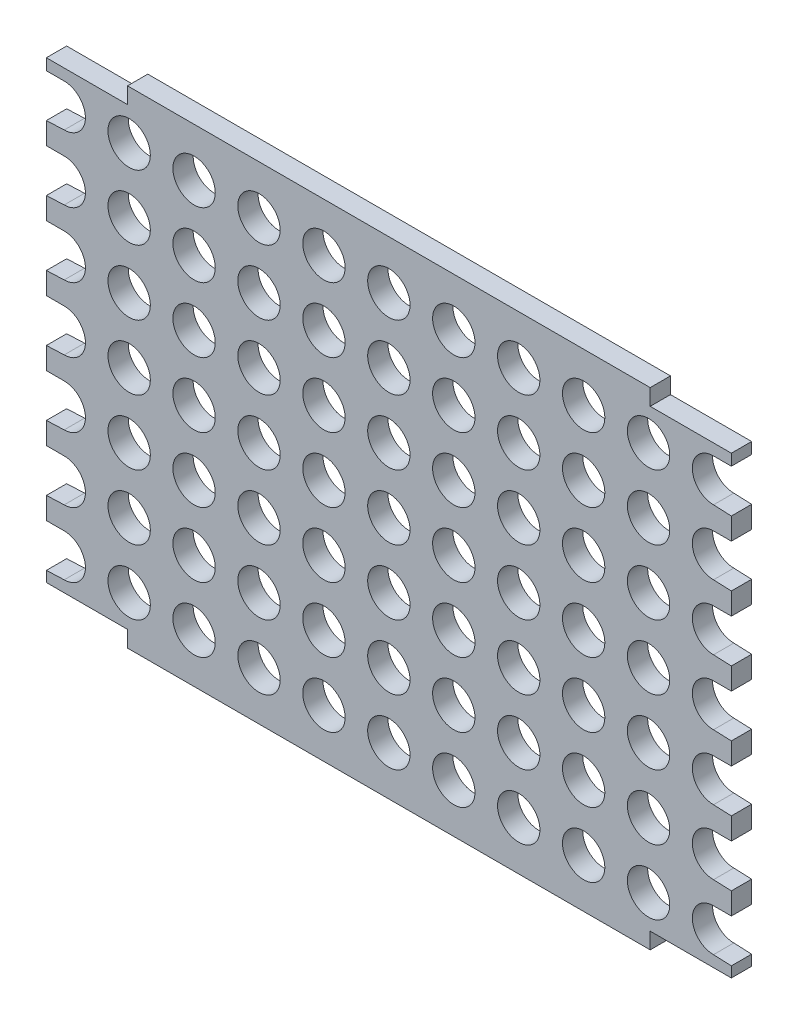
SolidWorks part; units mm, degrees
material "Nylon 6/10"
ref_plane "Front Plane" through (0, 0, 0) normal (0, 0, 1) x (1, 0, 0)
ref_plane "Top Plane" through (0, 0, 0) normal (0, 1, 0) x (1, 0, 0)
ref_plane "Right Plane" through (0, 0, 0) normal (1, 0, 0) x (0, 0, -1)
sketch "Sketch1" plane through (0, 0, 0) normal (0, 0, 1) x (1, 0, 0)
  line L1 (-53.594, -38.1) -> (53.594, -38.1)
  line L2 (-53.594, -38.1) -> (-53.594, 38.1)
  line L3 (-53.594, 38.1) -> (53.594, 38.1)
  line L4 (53.594, -38.1) -> (53.594, 38.1)
  line L5 (-53.594, -38.1) -> (53.594, 38.1) construction
  line L6 (-53.594, 38.1) -> (53.594, -38.1) construction
  point P0 (0, 0)
  dimension "D1" = 107.188
  dimension "D2" = 76.2
extrude "Extrude1" add sketch "Sketch1" along normal blind 3.175
sketch "Sketch3" plane through (0, 0, 3.175) normal (0, 0, 1) x (1, 0, 0)
  point P0 (0, 0)
sketch "Sketch7" plane through (0, 0, 3.175) normal (0, 0, 1) x (1, 0, 0)
  line L1 (-53.594, 38.1) -> (-40.894, 38.1)
  line L2 (-53.594, 38.1) -> (-53.594, 35.56)
  line L3 (-53.594, 35.56) -> (-40.894, 35.56)
  line L4 (-40.894, 38.1) -> (-40.894, 35.56)
  line L5 (-53.594, -38.1) -> (-40.894, -38.1)
  line L6 (-53.594, -38.1) -> (-53.594, -35.56)
  line L7 (-53.594, -35.56) -> (-40.894, -35.56)
  line L8 (-40.894, -38.1) -> (-40.894, -35.56)
  dimension "D1" = 12.7
  dimension "D2" = 2.54
extrude "Extrude2" cut sketch "Sketch7" against normal through all
mirror "Mirror1" about plane through (0, 0, 0) normal (1, 0, 0) of "Extrude2"
hole_wizard "G (0.261) Diameter Hole1" positions "Sketch6" profile "Sketch5" hole size "G" standard "Ansi Inch"
sketch "Sketch6" plane through (0, 0, 3.175) normal (0, 0, 1) x (1, 0, 0)
  point P2 (0, 0)
sketch "Sketch5" plane through (0, 0, 3.175) normal (1, 0, 0) x (0, -1, 0)
  line L0 (0, 0) -> (0, 17.2317)
  line L1 (0, 17.2317) -> (3.3147, 15.24)
  line L2 (3.3147, 15.24) -> (3.3147, 0)
  line L5 (3.3147, 0) -> (0, 0)
  line L10 (0, 17.2317) -> (-3.3147, 15.24) construction
  line L11 (0, -6.35) -> (0, 107.95) construction
  dimension "Hole Dia." = 6.6294
  dimension "Hole Depth" = 15.24
  dimension "Drill Angle" = 118
pattern_linear "LPattern1" count 6 spacing 10.16 along (1, 0, 0) count 6 spacing 10.16 along (-1, 0, 0) of "G (0.261) Diameter Hole1"
pattern_linear "LPattern2" count 4 spacing 10.16 along (0, -1, 0) count 4 spacing 10.16 along (0, 1, 0) of "LPattern1", "G (0.261) Diameter Hole1"
sketch "Sketch8" plane through (0, 0, 3.175) normal (0, 0, 1) x (1, 0, 0)
  line L0 (-50.8, -27.1653) -> (-50.8, -33.7947)
  line L1 (-50.8, -33.7947) -> (-53.594, -33.9117)
  line L2 (-53.594, -32.2635) -> (-53.594, -35.56) construction
  line L3 (-53.594, -33.9117) -> (-53.594, -27.1653)
  line L4 (-53.594, -22.1035) -> (-53.594, -28.6965) construction
  line L5 (-53.594, -27.1653) -> (-50.8, -27.1653)
  arc A0 (-53.594, -32.2635) -> (-53.594, -28.6965) centre (-50.8, -30.48) ccw construction
extrude "Extrude3" cut sketch "Sketch8" against normal through all
pattern_linear "LPattern3" count 7 spacing 10.16 along (0, 1, 0) of "Extrude3"
mirror "Mirror2" about plane through (0, 0, 0) normal (1, 0, 0) of "LPattern3", "Extrude3"
